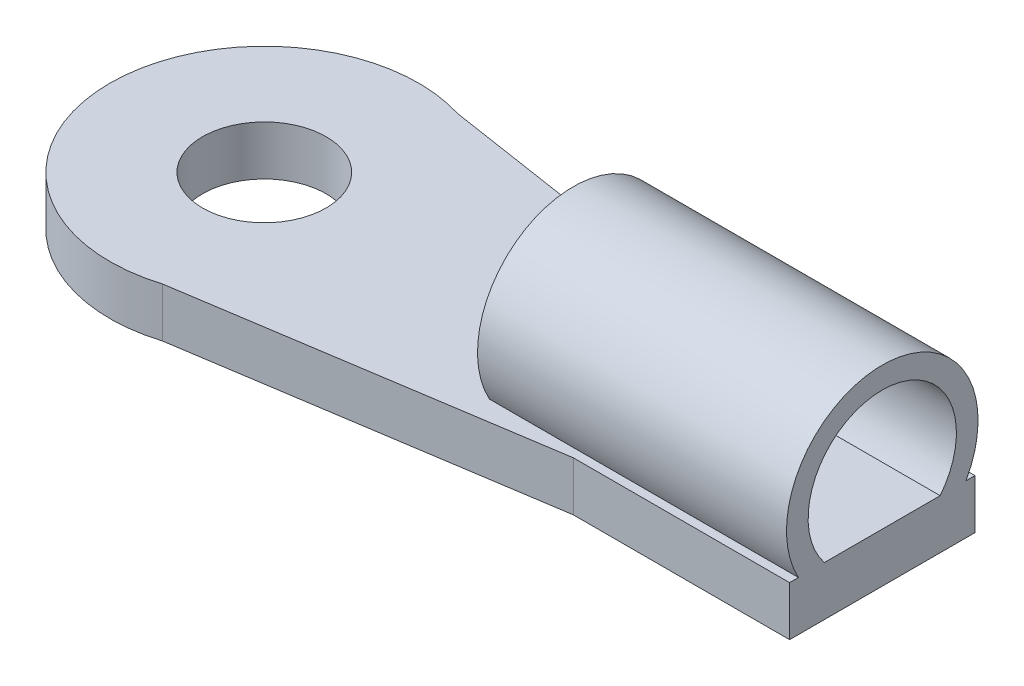
SolidWorks part; units mm, degrees
ref_plane "Front Plane" through (0, 0, 0) normal (0, 0, 1) x (1, 0, 0)
ref_plane "Top Plane" through (0, 0, 0) normal (0, 1, 0) x (1, 0, 0)
ref_plane "Right Plane" through (0, 0, 0) normal (1, 0, 0) x (0, 0, -1)
sketch "Sketch1" plane through (0, 0, 0) normal (0, 1, 0) x (1, 0, 0)
  line L0 (6.5, 1.5) -> (0.7387, 2.3884)
  line L5 (6.5, -1.5) -> (0.7387, -2.3884)
  line L7 (6.5, 1.5) -> (10, 1.5)
  line L9 (6.5, -1.5) -> (10, -1.5)
  line L10 (10, 1.5) -> (10, -1.5)
  circle A0 centre (0, 0) radius 1
  arc A1 (0.7387, 2.3884) -> (0.7387, -2.3884) centre (0, 0) ccw
extrude "Boss-Extrude1" add sketch "Sketch1" along normal blind 0.8
sketch "Sketch5" plane through (10, 0, 0) normal (1, 0, 0) x (0, 0, -1)
  line L0 (0, 0.8) -> (0, 1.55)
  line L1 (-1.5, 0.8) -> (1.5, 0.8) construction
  circle A0 centre (0, 1.55) radius 1.55
  circle A1 centre (0, 1.55) radius 1.2
  line M4 (1.5, 0.8) -> (-1.5, 0.8)
extrude "Boss-Extrude4" add sketch "Sketch5" against normal blind 5 contours A1 A0 M4
